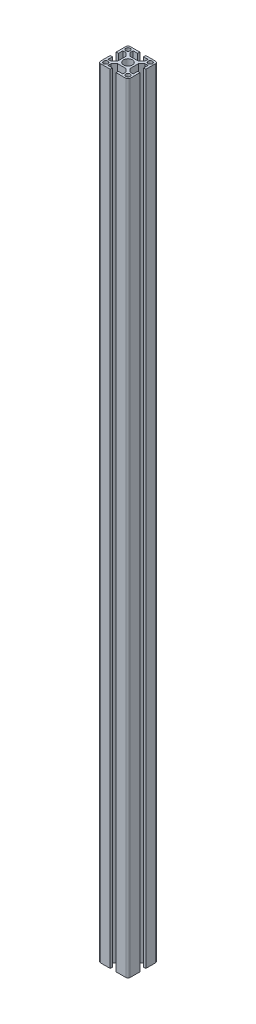
SolidWorks part; units mm, degrees
material "6061-T6 (SS)"
ref_plane "Front Plane" through (0, 0, 0) normal (0, 0, 1) x (1, 0, 0)
ref_plane "Top Plane" through (0, 0, 0) normal (0, 1, 0) x (1, 0, 0)
ref_plane "Right Plane" through (0, 0, 0) normal (1, 0, 0) x (0, 0, -1)
sketch "Sketch1" plane through (0, 0, 0) normal (0, 1, 0) x (1, 0, 0)
  line L0 (-20, -4) -> (-17, -4)
  line L1 (20, 0) -> (-20, 0) construction
  line L2 (0, 20) -> (0, -20) construction
  line L3 (-4, -20) -> (-17, -20)
  line L4 (-20, -4) -> (-20, -17)
  line L5 (-17, -4) -> (-17, -10)
  line L6 (-17, -10) -> (-13, -10)
  line L7 (-13, -10) -> (-8.5, -5.5)
  line L8 (-8.5, -5.5) -> (-8.5, 5.5)
  line L9 (-20, -20) -> (0, 0) construction
  line L10 (-5.5, -8.5) -> (5.5, -8.5)
  line L11 (-10, -13) -> (-5.5, -8.5)
  line L12 (-10, -17) -> (-10, -13)
  line L13 (-4, -17) -> (-10, -17)
  line L14 (-4, -20) -> (-4, -17)
  line L16 (-20, 20) -> (0, 0) construction
  line L17 (-4, 20) -> (-17, 20)
  line L18 (-4, 20) -> (-4, 17)
  line L19 (-4, 17) -> (-10, 17)
  line L20 (-10, 17) -> (-10, 13)
  line L21 (-10, 13) -> (-5.5, 8.5)
  line L22 (-5.5, 8.5) -> (5.5, 8.5)
  line L23 (-13, 10) -> (-8.5, 5.5)
  line L24 (-17, 10) -> (-13, 10)
  line L25 (-17, 4) -> (-17, 10)
  line L26 (-20, 4) -> (-20, 17)
  line L28 (-20, 4) -> (-17, 4)
  line L29 (20, 20) -> (0, 0) construction
  line L30 (20, -20) -> (0, 0) construction
  line L31 (20, 4) -> (17, 4)
  line L32 (4, 20) -> (17, 20)
  line L33 (20, 4) -> (20, 17)
  line L34 (17, 4) -> (17, 10)
  line L35 (17, 10) -> (13, 10)
  line L36 (13, 10) -> (8.5, 5.5)
  line L37 (10, 13) -> (5.5, 8.5)
  line L38 (10, 17) -> (10, 13)
  line L39 (4, 17) -> (10, 17)
  line L40 (4, 20) -> (4, 17)
  line L42 (4, -20) -> (17, -20)
  line L43 (4, -20) -> (4, -17)
  line L44 (4, -17) -> (10, -17)
  line L45 (10, -17) -> (10, -13)
  line L46 (10, -13) -> (5.5, -8.5)
  line L47 (8.5, -5.5) -> (8.5, 5.5)
  line L48 (13, -10) -> (8.5, -5.5)
  line L49 (17, -10) -> (13, -10)
  line L50 (17, -4) -> (17, -10)
  line L51 (20, -4) -> (20, -17)
  line L53 (20, -4) -> (17, -4)
  circle A0 centre (0, 0) radius 6
  circle A1 centre (-15, -15) radius 3
  arc A2 (-17, -20) -> (-20, -17) centre (-17, -17) cw
  arc A3 (-17, 20) -> (-20, 17) centre (-17, 17) ccw
  circle A4 centre (-15, 15) radius 3
  circle A5 centre (15, 15) radius 3
  arc A6 (17, 20) -> (20, 17) centre (17, 17) cw
  arc A7 (17, -20) -> (20, -17) centre (17, -17) ccw
  circle A8 centre (15, -15) radius 3
  point P11 (-20, -20)
  point P25 (0, 0)
  point P26 (0, 0)
  point P41 (-8.5, 0)
  point P64 (0, 8.5)
  point P72 (0, -8.5)
  point P77 (8.5, 0)
  dimension "D3" = 6
  dimension "D4" = 6
  dimension "D5" = 3
  dimension "D2" = 20
  dimension "D6" = 5
  dimension "D7" = 5
  dimension "D8" = 3
  dimension "D9" = 16
  dimension "D10" = 10
  dimension "D11" = 45
  dimension "D12" = 8.5
  dimension "D13" = 4
extrude "Boss-Extrude1" add sketch "Sketch1" along normal blind 1050
